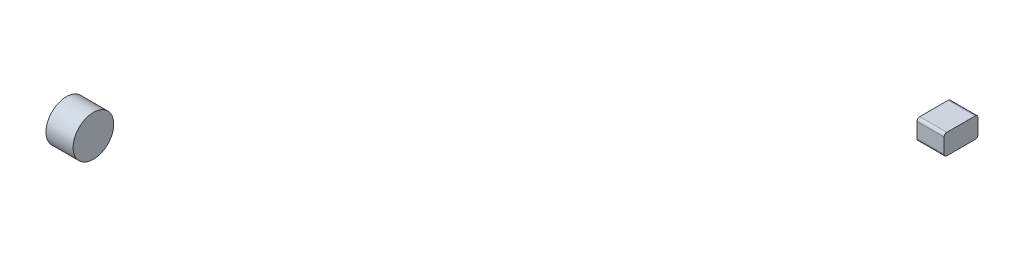
SolidWorks part; units mm, degrees
ref_plane "Front Plane" through (0, 0, 0) normal (0, 0, 1) x (1, 0, 0)
ref_plane "Top Plane" through (0, 0, 0) normal (0, 1, 0) x (1, 0, 0)
ref_plane "Right Plane" through (0, 0, 0) normal (1, 0, 0) x (0, 0, -1)
sketch "Sketch1" plane through (0, 0, 0) normal (1, 0, 0) x (0, 0, -1)
  circle A0 centre (-15.24, -25.4) radius 1.905
  dimension "D1" = 25.4
  dimension "D2" = 15.24
extrude "Extrude1" add sketch "Sketch1" against normal blind 2.54
ref_plane "Plane1" through (63.5, 0, 0) normal (1, 0, 0) x (0, 0, -1)
sketch "Sketch2" plane through (63.5, 0, 0) normal (1, 0, 0) x (0, 0, -1)
  line L7 (-1.3335, 0.9525) -> (1.3335, 0.9525)
  line L8 (-1.5875, 0.6985) -> (-1.5875, -0.6985)
  line L9 (-1.3335, -0.9525) -> (1.3335, -0.9525)
  line L10 (1.5875, 0.6985) -> (1.5875, -0.6985)
  arc A0 (-1.3335, 0.9525) -> (-1.5875, 0.6985) centre (-1.3335, 0.6985) ccw
  arc A1 (1.3335, 0.9525) -> (1.5875, 0.6985) centre (1.3335, 0.6985) cw
  arc A2 (1.3335, -0.9525) -> (1.5875, -0.6985) centre (1.3335, -0.6985) ccw
  arc A3 (-1.5875, -0.6985) -> (-1.3335, -0.9525) centre (-1.3335, -0.6985) ccw
  point P5 (0, 0)
  dimension "D1" = 0.254
extrude "Extrude2" add sketch "Sketch2" along normal blind 2.54
sketch "Sketch3" plane through (0, 0, 0) normal (0, 0, 1) x (1, 0, 0)
  line L0 (0, -25.4) -> (1.7038, -25.4)
  line L1 (0, -27.305) -> (0, -23.495) construction
  line L2 (63.5, 0) -> (54.5045, 0)
  line L3 (63.5, 0.6985) -> (63.5, -0.6985) construction
  arc A0 (11.8093, -23.3032) -> (25.2184, -12.7316) centre (-1.481, 7.3442) ccw
  arc A1 (31.9709, -6.5118) -> (54.5045, 0) centre (54.5045, -42.2437) cw
  arc A2 (25.2184, -12.7316) -> (31.9709, -6.5118) centre (45.5197, -27.9964) cw
  arc A3 (1.7038, -25.4) -> (11.8093, -23.3032) centre (1.7038, 0) ccw
  dimension "D1" = 25.4
sketch "Sketch4" plane through (0, 0, 0) normal (0, 1, 0) x (1, 0, 0)
  line L0 (0, -15.24) -> (3.5183, -15.24)
  line L1 (0, -17.145) -> (0, -13.335) construction
  line L2 (63.5, 0) -> (61.5041, 0)
  line L3 (63.5, 0) -> (54.5045, 0) construction
  arc A0 (7.2294, -15.1043) -> (26.9135, -10.6956) centre (2.2064, 53.4709) ccw
  arc A1 (40.655, -3.699) -> (31.3475, -8.469) centre (57.1311, -47.3142) ccw
  arc A2 (26.9135, -10.6956) -> (31.3475, -8.469) centre (17.7865, 13.0079) ccw
  arc A3 (3.5183, -15.24) -> (7.2294, -15.1043) centre (3.5183, 35.56) ccw
  arc A4 (40.655, -3.699) -> (61.5041, 0) centre (67.7102, -95.5856) cw
  dimension "D1" = 25.4
  dimension "D2" = 50.8
